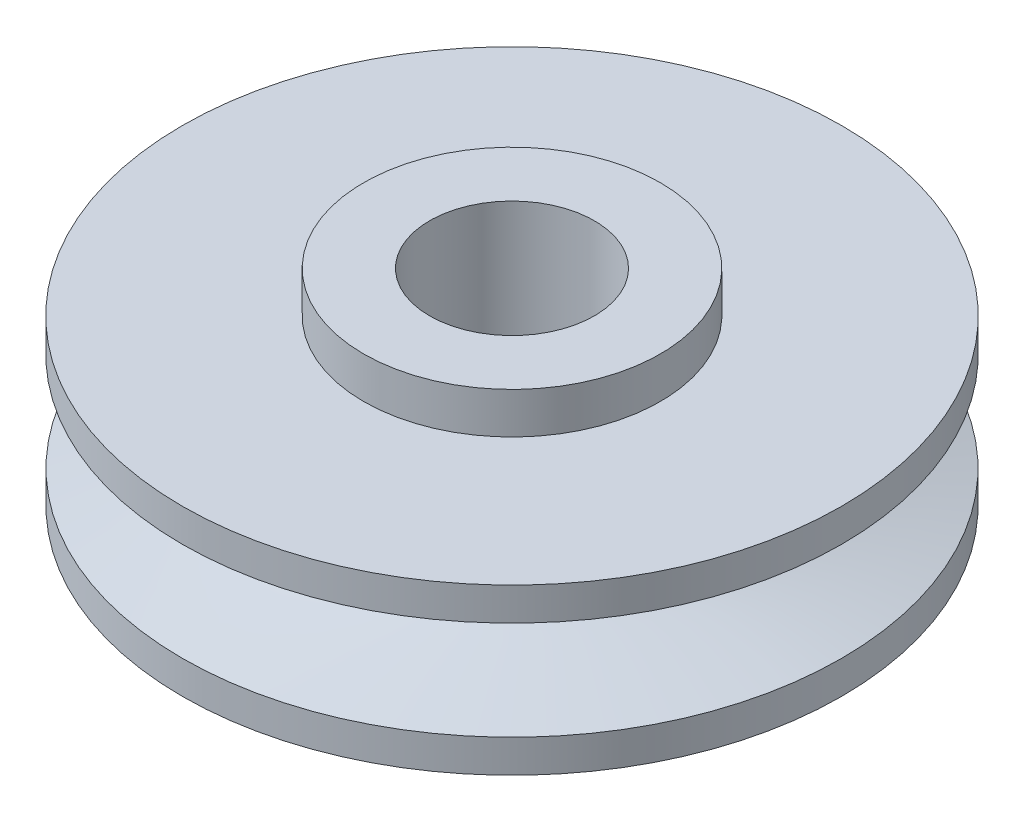
SolidWorks part; units mm, degrees
ref_plane "前视基准面" through (0, 0, 0) normal (0, 0, 1) x (1, 0, 0)
ref_plane "上视基准面" through (0, 0, 0) normal (0, 1, 0) x (1, 0, 0)
ref_plane "右视基准面" through (0, 0, 0) normal (1, 0, 0) x (0, 0, -1)
sketch "草图1" plane through (0, 0, 0) normal (0, 0, 1) x (1, 0, 0)
  line L0 (0, 2.0786) -> (0, -2.1269) construction
  line L1 (1, -1.5) -> (1.8, -1.5)
  line L2 (1.8, -1.5) -> (1.8, -1)
  line L3 (1, 1.5) -> (1, -1.5)
  line L4 (1.8, -1) -> (3.9979, -1)
  line L5 (4, 0.6) -> (4, 1)
  line L6 (3.9979, -1) -> (3.9979, -0.6)
  line L7 (4, 1) -> (1.8, 1)
  line L8 (1.8, 1) -> (1.8, 1.5)
  line L9 (1.8, 1.5) -> (1, 1.5)
  line L10 (0, 0) -> (4.9225, 0) construction
  conic Q0 (4, 0.6) -> (3.9979, -0.6) control (2.1686, 0) rho 0.728124
  point P14 (0, 2)
  dimension "D1" = 1
  dimension "D2" = 4
  dimension "D3" = 0.6
  dimension "D4" = 0.6
  dimension "D5" = 3
  dimension "D6" = 1.5
  dimension "D7" = 2
  dimension "D8" = 1
revolve "旋转9" add sketch "草图1" angle 360 about L0
